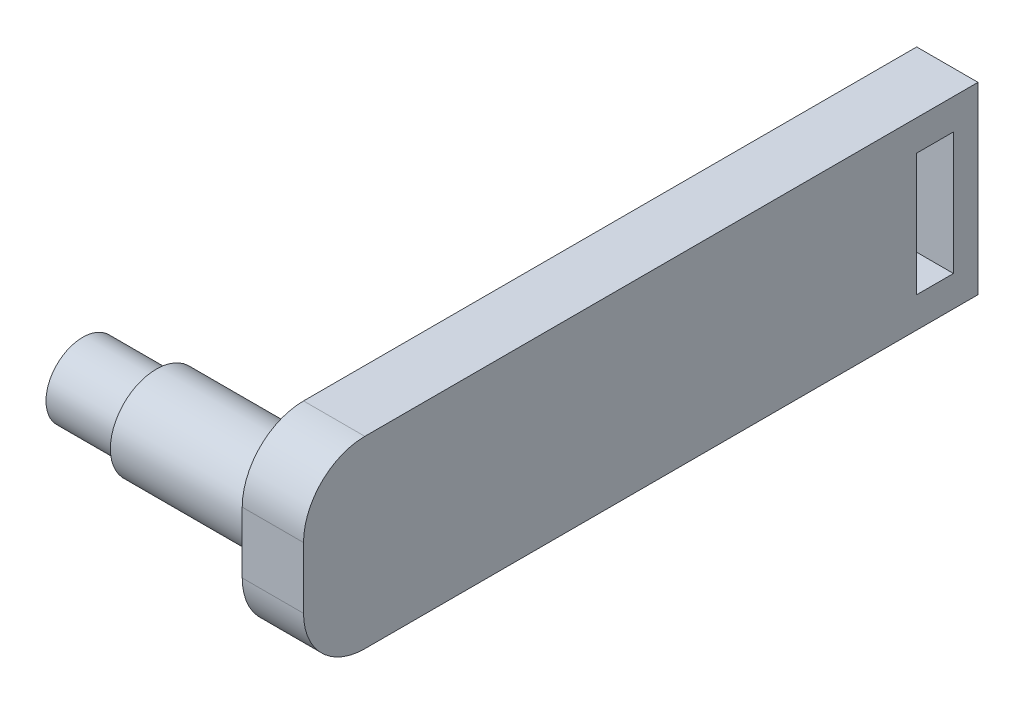
SolidWorks part; units mm, degrees
ref_plane "Front Plane" through (0, 0, 0) normal (0, 0, 1) x (1, 0, 0)
ref_plane "Top Plane" through (0, 0, 0) normal (0, 1, 0) x (1, 0, 0)
ref_plane "Right Plane" through (0, 0, 0) normal (1, 0, 0) x (0, 0, -1)
sketch "Sketch1" plane through (0, 0, 0) normal (0, 1, 0) x (1, 0, 0)
  line L1 (-61.8805, -26.2097) -> (-56.8805, -26.2097)
  line L2 (-61.8805, -26.2097) -> (-61.8805, 28.7903)
  line L3 (-61.8805, 28.7903) -> (-56.8805, 28.7903)
  line L4 (-56.8805, -26.2097) -> (-56.8805, 28.7903)
  line L6 (-56.8805, 28.7903) -> (-56.8805, 23.7903)
  dimension "D5" = 5
extrude "Boss-Extrude1" add sketch "Sketch1" along normal blind 15 contours L1 L4 L3 L2
sketch "Sketch2" plane through (-61.8805, 0, 0) normal (-1, 0, 0) x (0, 0, 1)
  line L2 (26.2097, 0) -> (-28.7903, 0) construction
  line L3 (-28.7903, 15) -> (-28.7903, 0) construction
  line L5 (-26.7903, 2.5) -> (-23.7903, 2.5)
  line L6 (-26.7903, 2.5) -> (-26.7903, 12.5)
  line L7 (-26.7903, 12.5) -> (-23.7903, 12.5)
  line L8 (-23.7903, 2.5) -> (-23.7903, 12.5)
  dimension "D4" = 2.5
  dimension "D5" = 10
  dimension "D6" = 2
  dimension "D7" = 3
fillet "Fillet1" radius 5 2 edges at (-59.3805, 15, 26.2097) (-59.3805, 0, 26.2097)
sketch "Sketch3" plane through (-61.8805, 0, 0) normal (-1, 0, 0) x (0, 0, 1)
  line L3 (21.2097, 15) -> (-28.7903, 15) construction
  line L4 (26.2097, 10) -> (26.2097, 5) construction
  circle A1 centre (21.2097, 7.5) radius 3.75
  dimension "D1" = 7.5
  dimension "D2" = 5
  dimension "D3" = 7.5
extrude "Cut-Extrude1" cut sketch "Sketch2" against normal up to surface (5 mm away) up to face at (-56.8805, 7.5, 6.5549)
extrude "Boss-Extrude2" add sketch "Sketch3" along normal blind 12
sketch "Sketch4" plane through (-73.8805, 0, 0) normal (-1, 0, 0) x (0, 0, 1)
  circle A0 centre (21.2097, 7.5) radius 3
  circle A1 centre (21.2097, 7.5) radius 1.75
extrude "Boss-Extrude3" add sketch "Sketch4" along normal blind 6
